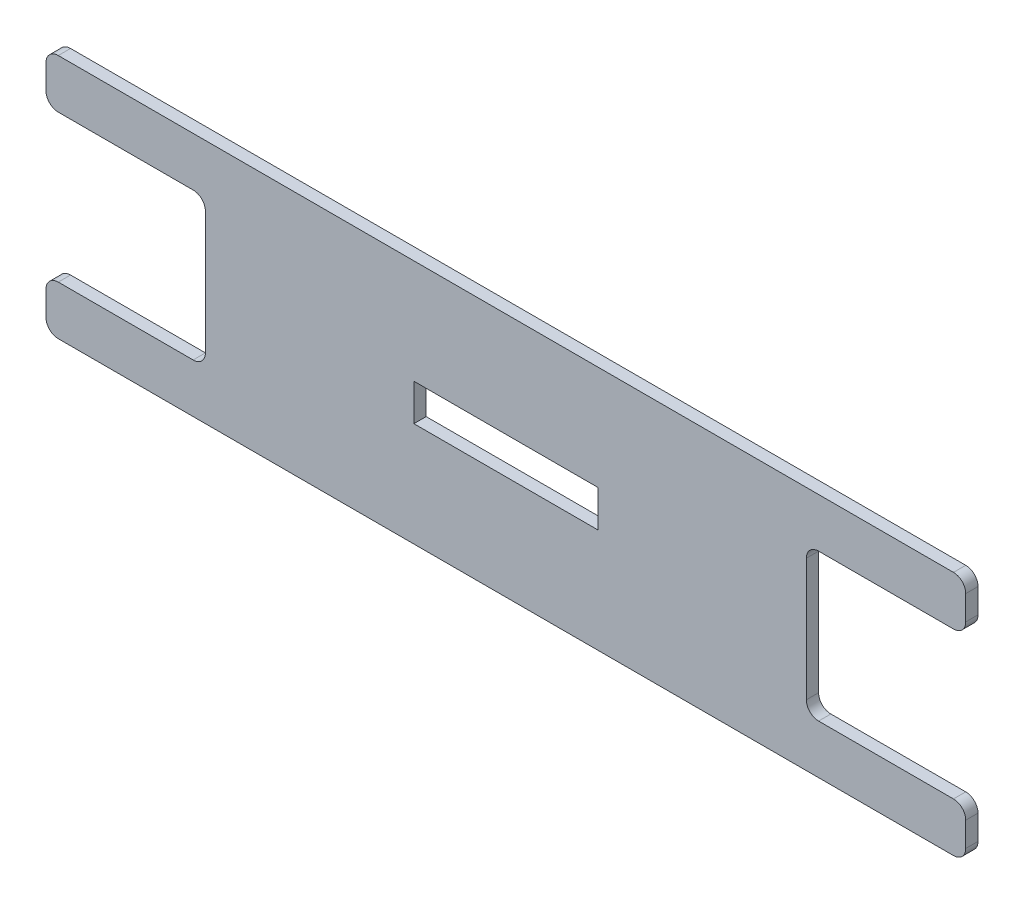
SolidWorks part; units mm, degrees
material "6061 Alloy"
ref_plane "Front Plane" through (0, 0, 0) normal (0, 0, 1) x (1, 0, 0)
ref_plane "Top Plane" through (0, 0, 0) normal (0, 1, 0) x (1, 0, 0)
ref_plane "Right Plane" through (0, 0, 0) normal (1, 0, 0) x (0, 0, -1)
sketch "Sketch1" plane through (0, 0, 0) normal (0, 0, 1) x (1, 0, 0)
  line L1 (37.5, -10) -> (-37.5, -10)
  line L2 (37.5, -10) -> (37.5, 10)
  line L3 (37.5, 10) -> (-37.5, 10)
  line L4 (-37.5, -10) -> (-37.5, 10)
  line L5 (37.5, -10) -> (-37.5, 10) construction
  line L6 (37.5, 10) -> (-37.5, -10) construction
  point P0 (0, 0)
  dimension "D1" = 20
  dimension "D2" = 75
extrude "Boss-Extrude1" add sketch "Sketch1" along normal blind 1
sketch "Sketch2" plane through (0, 0, 1) normal (0, 0, 1) x (1, 0, 0)
  line L0 (-37.5, 10) -> (-37.5, -10) construction
  line L1 (-37.5, 6) -> (-24.5, 6)
  line L2 (-24.5, 6) -> (-24.5, -6)
  line L3 (-24.5, -6) -> (-37.5, -6)
  arc A0 (-37.5, 6) -> (-37.5, -6) centre (-37.5, 0) ccw
  dimension "D1" = 12
  dimension "D2" = 13
extrude "Cut-Extrude1" cut sketch "Sketch2" against normal through all
fillet "Fillet1" radius 1 6 edges at (-24.5, -6, 0.5) (-24.5, 6, 0.5) (-37.5, -10, 0.5) (-37.5, -6, 0.5) (-37.5, 10, 0.5) (-37.5, 6, 0.5)
mirror "Mirror1" about plane through (0, 0, 0) normal (1, 0, 0) of "Cut-Extrude1"
fillet "Fillet2" radius 1 6 edges at (37.5, -10, 0.5) (37.5, -6, 0.5) (24.5, -6, 0.5) (24.5, 6, 0.5) (37.5, 6, 0.5) (37.5, 10, 0.5)
sketch "Sketch3" plane through (0, 0, 1) normal (0, 0, 1) x (1, 0, 0)
  line L1 (7.5, -1.5) -> (-7.5, -1.5)
  line L2 (7.5, -1.5) -> (7.5, 1.5)
  line L3 (7.5, 1.5) -> (-7.5, 1.5)
  line L4 (-7.5, -1.5) -> (-7.5, 1.5)
  line L5 (7.5, -1.5) -> (-7.5, 1.5) construction
  line L6 (7.5, 1.5) -> (-7.5, -1.5) construction
  point P0 (0, 0)
  dimension "D1" = 15
  dimension "D2" = 3
extrude "Cut-Extrude2" cut sketch "Sketch3" against normal blind 1.25
